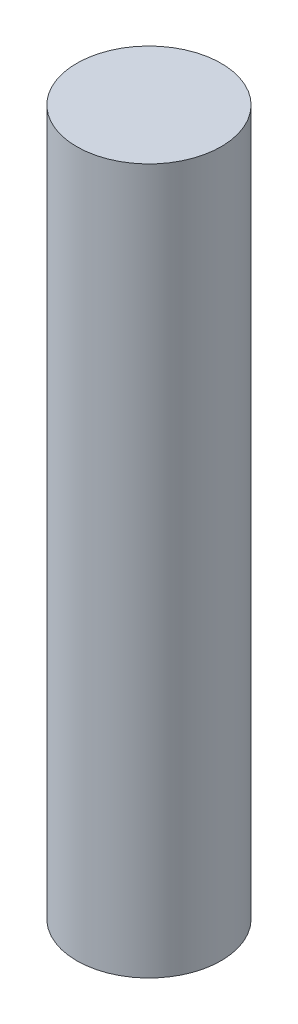
SolidWorks part; units mm, degrees
material "1023 Carbon Steel Sheet (SS)"
ref_plane "Front Plane" through (0, 0, 0) normal (0, 0, 1) x (1, 0, 0)
ref_plane "Top Plane" through (0, 0, 0) normal (0, 1, 0) x (1, 0, 0)
ref_plane "Right Plane" through (0, 0, 0) normal (1, 0, 0) x (0, 0, -1)
other "Center of Mass"
sketch "Sketch1" plane through (0, 0, 0) normal (0, 1, 0) x (1, 0, 0)
  circle A0 centre (0, 0) radius 12.5
  dimension "D1" = 25
extrude "Boss-Extrude1" add sketch "Sketch1" along normal blind 77 and the other way blind 45
equation "\"test\"= \"SW-Density\""
